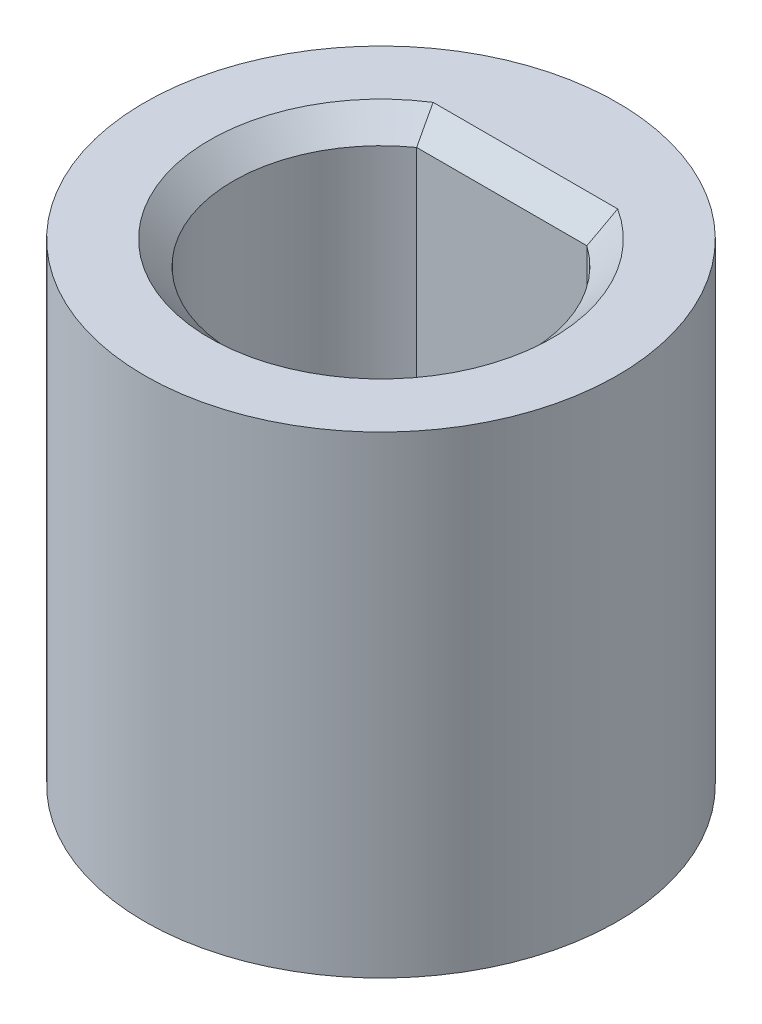
SolidWorks part; units mm, degrees
ref_plane "Front Plane" through (0, 0, 0) normal (0, 0, 1) x (1, 0, 0)
ref_plane "Top Plane" through (0, 0, 0) normal (0, 1, 0) x (1, 0, 0)
ref_plane "Right Plane" through (0, 0, 0) normal (1, 0, 0) x (0, 0, -1)
sketch "Sketch1" plane through (0, 0, 0) normal (0, 1, 0) x (1, 0, 0)
  circle A0 centre (0, 0) radius 5
  dimension "D1" = 10
extrude "Boss-Extrude1" add sketch "Sketch1" along normal blind 10
sketch "Sketch2" plane through (0, 10, 0) normal (0, 1, 0) x (1, 0, 0)
  line L0 (-1.7593, 2.43) -> (1.7593, 2.43) construction
  line L1 (-1.7993, 2.555) -> (1.7993, 2.555)
  arc A0 (-1.7593, 2.43) -> (1.7593, 2.43) centre (0, 0) ccw construction
  arc A1 (-1.7993, 2.555) -> (1.7993, 2.555) centre (0, 0) ccw
  dimension "D1" = 6
  dimension "D2" = 2.43
  dimension "D3" = 0.125
extrude "Cut-Extrude1" cut sketch "Sketch2" against normal blind 8
chamfer "Chamfer1" distance 0.5 angle 45 2 edges at (0, 10, 3.125) (0, 10, -2.555)
